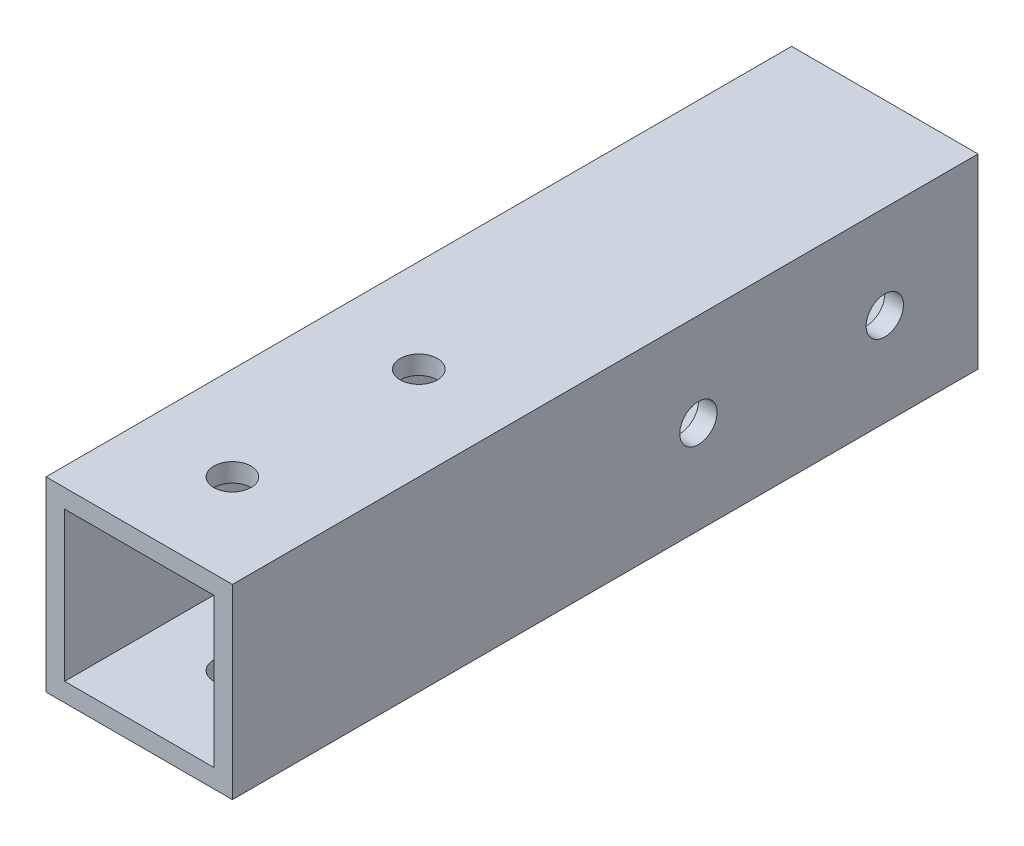
SolidWorks part; units mm, degrees
ref_plane "前视基准面" through (0, 0, 0) normal (0, 0, 1) x (1, 0, 0)
ref_plane "上视基准面" through (0, 0, 0) normal (0, 1, 0) x (1, 0, 0)
ref_plane "右视基准面" through (0, 0, 0) normal (1, 0, 0) x (0, 0, -1)
other "Configuration Table"
sketch "草图1" plane through (0, 0, 0) normal (0, 0, 1) x (1, 0, 0)
  line L0 (-8, -8) -> (-8, 8)
  line L1 (-10, -10) -> (10, -10)
  line L2 (-10, -10) -> (-10, 10)
  line L3 (-10, 10) -> (10, 10)
  line L4 (10, -10) -> (10, 10)
  line L5 (-10, -10) -> (10, 10) construction
  line L6 (-10, 10) -> (10, -10) construction
  line L7 (-8, 8) -> (8, 8)
  line L8 (8, -8) -> (8, 8)
  line L9 (-8, -8) -> (8, -8)
  point P0 (0, 0)
  dimension "D1" = 20
  dimension "D2" = 2
extrude "凸台-拉伸1" add sketch "草图1" along normal blind 80
sketch "草图2" plane through (10, 0, 0) normal (1, 0, 0) x (0, 0, -1)
  line L0 (16.7105, 0) -> (-118.1303, 0) construction
  line L1 (0, -10) -> (0, 10) construction
  line L2 (-10, 0) -> (-30, 0) construction
  circle A0 centre (-10, 0) radius 2
  circle A1 centre (-30, 0) radius 2
  arc A3 (-48, 0) -> (-52, 0) centre (-50, 0) ccw [skipped]
  dimension "D1" = 4
  dimension "D2" = 10
  dimension "D4" = 20
  dimension "D3" = 3
extrude "切除-拉伸1" cut sketch "草图2" against normal blind 100
sketch "草图3" plane through (0, -10, 0) normal (0, -1, 0) x (1, 0, 0)
  line L0 (0, 105.8089) -> (0, -8.0945) construction
  line L1 (-10, 80) -> (10, 80) construction
  circle A0 centre (0, 50) radius 2
  circle A1 centre (0, 70) radius 2
  dimension "D1" = 4
  dimension "D2" = 4
  dimension "D3" = 30
  dimension "D4" = 20
extrude "切除-拉伸2" cut sketch "草图3" against normal blind 100
